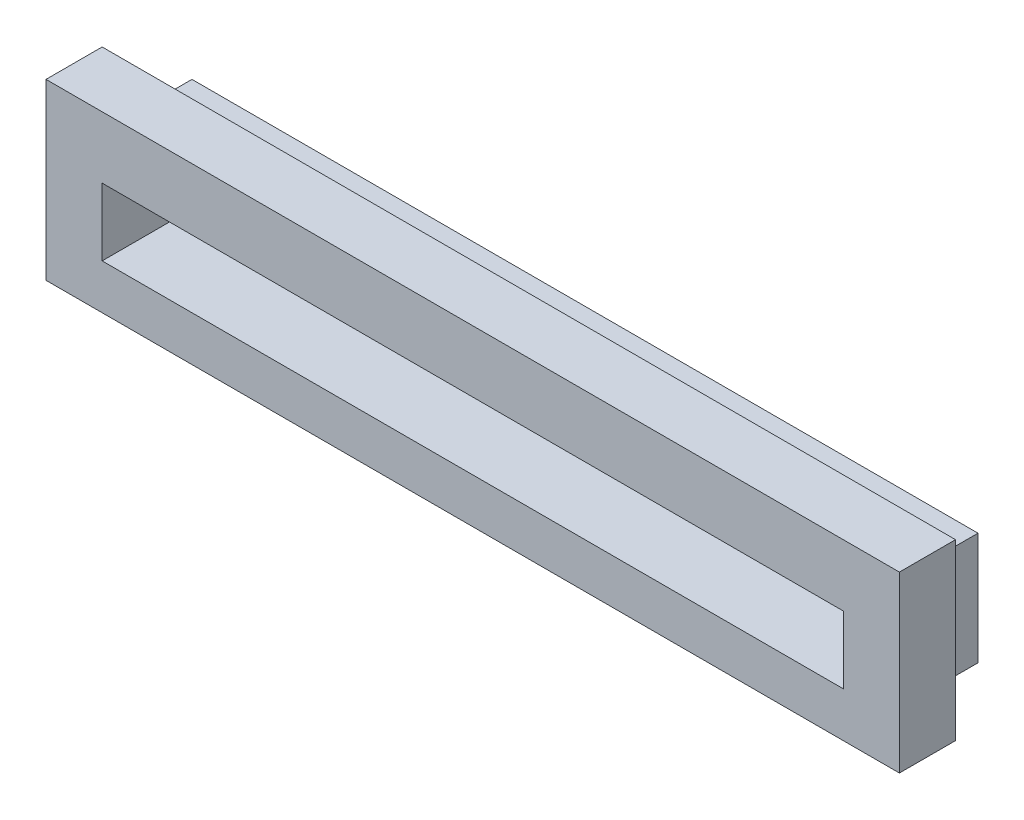
SolidWorks part; units mm, degrees
ref_plane "Front Plane" through (0, 0, 0) normal (0, 0, 1) x (1, 0, 0)
ref_plane "Top Plane" through (0, 0, 0) normal (0, 1, 0) x (1, 0, 0)
ref_plane "Right Plane" through (0, 0, 0) normal (1, 0, 0) x (0, 0, -1)
sketch "Sketch1" plane through (0, 0, 0) normal (0, 0, 1) x (1, 0, 0)
  line L1 (0, 0) -> (177.8, 0)
  line L2 (0, 0) -> (0, 25.4)
  line L3 (0, 25.4) -> (177.8, 25.4)
  line L4 (177.8, 0) -> (177.8, 25.4)
  line L5 (5.08, 20.32) -> (172.72, 20.32)
  line L6 (5.08, 20.32) -> (5.08, 5.08)
  line L7 (5.08, 5.08) -> (172.72, 5.08)
  line L8 (172.72, 20.32) -> (172.72, 5.08)
  dimension "D1" = 177.8
  dimension "D2" = 25.4
  dimension "D3" = 5.08
  dimension "D4" = 5.08
  dimension "D5" = 5.08
  dimension "D6" = 5.08
extrude "Boss-Extrude2" add sketch "Sketch1" along normal blind 25.4
sketch "Sketch3" plane through (0, 0, 25.4) normal (0, 0, 1) x (1, 0, 0)
  line L1 (-7.62, 34.29) -> (185.42, 34.29)
  line L2 (-7.62, 34.29) -> (-7.62, -5.08)
  line L3 (-7.62, -5.08) -> (185.42, -5.08)
  line L4 (185.42, 34.29) -> (185.42, -5.08)
  line L5 (0, 25.4) -> (177.8, 25.4)
  line L6 (0, 25.4) -> (0, 0)
  line L7 (0, 0) -> (177.8, 0)
  line L8 (177.8, 25.4) -> (177.8, 0)
  dimension "D1" = 8.89
  dimension "D2" = 7.62
  dimension "D3" = 7.62
  dimension "D4" = 5.08
extrude "Boss-Extrude3" add sketch "Sketch3" against normal blind 12.7
